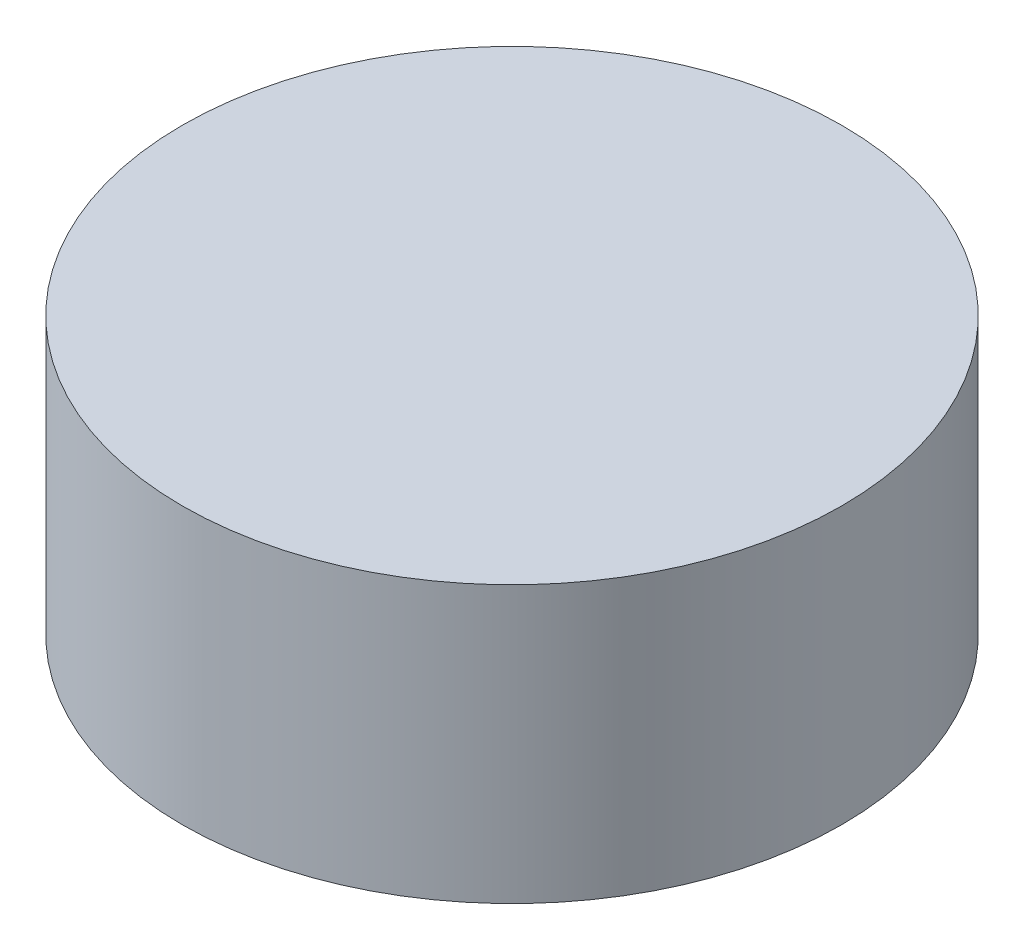
SolidWorks part; units mm, degrees
ref_plane "Front Plane" through (0, 0, 0) normal (0, 0, 1) x (1, 0, 0)
ref_plane "Top Plane" through (0, 0, 0) normal (0, 1, 0) x (1, 0, 0)
ref_plane "Right Plane" through (0, 0, 0) normal (1, 0, 0) x (0, 0, -1)
sketch "Sketch1" plane through (0, 0, 0) normal (0, 1, 0) x (1, 0, 0)
  circle A0 centre (0, 0) radius 20.32
  dimension "D1" = 40.64
extrude "Boss-Extrude1" add sketch "Sketch1" along normal blind 17.018
